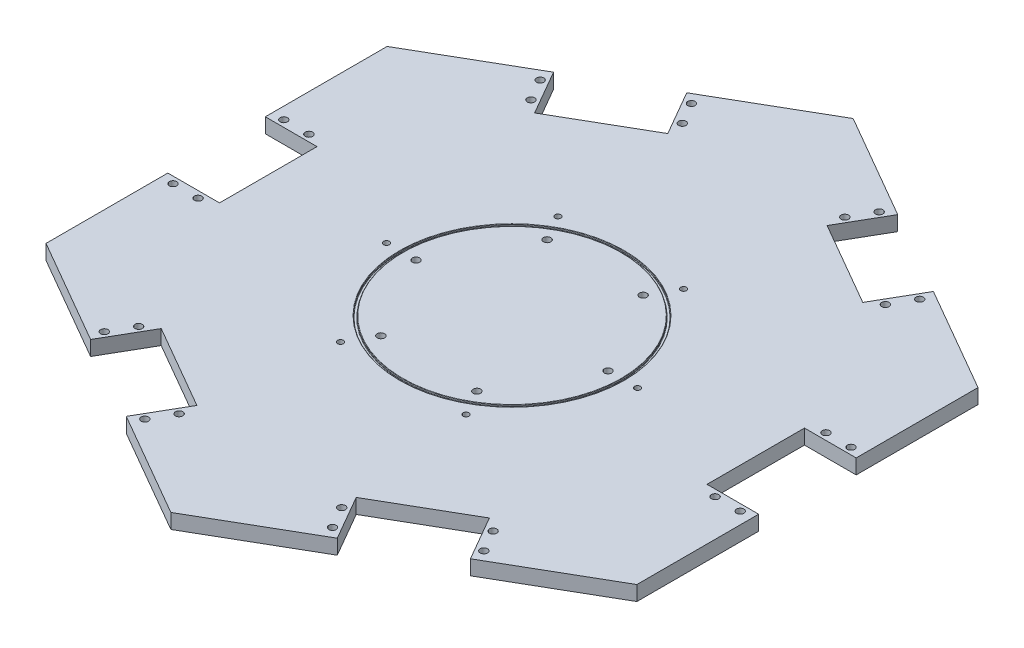
SolidWorks part; units mm, degrees
ref_plane "Front Plane" through (0, 0, 0) normal (0, 0, 1) x (1, 0, 0)
ref_plane "Top Plane" through (0, 0, 0) normal (0, 1, 0) x (1, 0, 0)
ref_plane "Right Plane" through (0, 0, 0) normal (1, 0, 0) x (0, 0, -1)
sketch "Sketch1" plane through (0, 0, 0) normal (0, 1, 0) x (1, 0, 0)
  line L0 (-200, 115.4701) -> (0, 230.9401)
  line L1 (-200, -115.4701) -> (200, -115.4701) construction
  line L2 (-200, -115.4701) -> (-200, 115.4701)
  line L3 (-200, 115.4701) -> (200, 115.4701) construction
  line L4 (200, -115.4701) -> (200, 115.4701)
  line L5 (-200, -115.4701) -> (200, 115.4701) construction
  line L6 (-200, 115.4701) -> (200, -115.4701) construction
  line L7 (0, 230.9401) -> (200, 115.4701)
  line L8 (200, -115.4701) -> (0, -230.9401)
  line L9 (0, -230.9401) -> (-200, -115.4701)
  point P0 (0, 0)
  point P8 (0, 245.7212)
  point P9 (0, 238.6781)
  dimension "D1" = 400
  dimension "D2" = 120
extrude "Boss-Extrude1" add sketch "Sketch1" along normal blind 10
sketch "Sketch2" plane through (0, 10, 0) normal (0, 1, 0) x (1, 0, 0)
  line L0 (175, -37.5) -> (175, 37.5) construction
  line L1 (200, 33) -> (165, 33)
  line L2 (200, 33) -> (200, -33)
  line L3 (200, -33) -> (165, -33)
  line L4 (165, 33) -> (165, -33)
  line L5 (128.5788, -156.7051) -> (111.0788, -126.3942)
  line L6 (200, 115.4701) -> (0, 230.9401)
  line L7 (0, 230.9401) -> (-200, 115.4701)
  line L8 (-200, 115.4701) -> (-200, -115.4701)
  line L9 (-200, -115.4701) -> (0, -230.9401)
  line L10 (0, -230.9401) -> (200, -115.4701)
  line L11 (200, -115.4701) -> (200, 115.4701)
  line L12 (200, 115.4701) -> (0, 230.9401)
  line L13 (0, 230.9401) -> (-200, 115.4701)
  line L14 (-200, 115.4701) -> (-200, -115.4701)
  line L15 (-200, -115.4701) -> (0, -230.9401)
  line L16 (0, -230.9401) -> (200, -115.4701)
  line L17 (200, -115.4701) -> (200, 115.4701)
  line L18 (111.0788, -126.3942) -> (53.9212, -159.3942)
  line L19 (71.4212, -189.7051) -> (53.9212, -159.3942)
  line L20 (-71.4212, -189.7051) -> (-53.9212, -159.3942)
  line L21 (-53.9212, -159.3942) -> (-111.0788, -126.3942)
  line L22 (-128.5788, -156.7051) -> (-111.0788, -126.3942)
  line L23 (-200, -33) -> (-165, -33)
  line L24 (-165, -33) -> (-165, 33)
  line L25 (-200, 33) -> (-165, 33)
  line L26 (-128.5788, 156.7051) -> (-111.0788, 126.3942)
  line L27 (-111.0788, 126.3942) -> (-53.9212, 159.3942)
  line L28 (-71.4212, 189.7051) -> (-53.9212, 159.3942)
  line L29 (71.4212, 189.7051) -> (53.9212, 159.3942)
  line L30 (53.9212, 159.3942) -> (111.0788, 126.3942)
  line L31 (128.5788, 156.7051) -> (111.0788, 126.3942)
  circle A0 centre (175, 37.5) radius 2.5
  circle A1 centre (192, 37.5) radius 2.5
  circle A2 centre (175, -37.5) radius 2.5
  circle A3 centre (192, -37.5) radius 2.5
  circle A4 centre (119.976, -132.8044) radius 2.5
  circle A5 centre (128.476, -147.5269) radius 2.5
  circle A6 centre (55.024, -170.3044) radius 2.5
  circle A7 centre (63.524, -185.0269) radius 2.5
  circle A8 centre (-55.024, -170.3044) radius 2.5
  circle A9 centre (-63.524, -185.0269) radius 2.5
  circle A10 centre (-119.976, -132.8044) radius 2.5
  circle A11 centre (-128.476, -147.5269) radius 2.5
  circle A12 centre (-175, -37.5) radius 2.5
  circle A13 centre (-192, -37.5) radius 2.5
  circle A14 centre (-175, 37.5) radius 2.5
  circle A15 centre (-192, 37.5) radius 2.5
  circle A16 centre (-119.976, 132.8044) radius 2.5
  circle A17 centre (-128.476, 147.5269) radius 2.5
  circle A18 centre (-55.024, 170.3044) radius 2.5
  circle A19 centre (-63.524, 185.0269) radius 2.5
  circle A20 centre (55.024, 170.3044) radius 2.5
  circle A21 centre (63.524, 185.0269) radius 2.5
  circle A22 centre (119.976, 132.8044) radius 2.5
  circle A23 centre (128.476, 147.5269) radius 2.5
  point P10 (165, 0)
  point P20 (175, 0)
  point P83 (0, 0)
  dimension "D6" = 5
  dimension "D2" = 66
  dimension "D3" = 35
  dimension "D4" = 75
  dimension "D5" = 17
  dimension "D7" = 10
  dimension "D1" = 0
  dimension "D8" = 6
extrude "Cut-Extrude1" cut sketch "Sketch2" against normal through all both and the other way through all
sketch "Sketch3" plane through (0, 0, 0) normal (0, 0, 1) x (1, 0, 0)
  line L0 (74.11, 10) -> (74.11, 8.984)
  line L1 (0, 10) -> (71.4212, 10) construction
  line L2 (74.364, 8.73) -> (75.636, 8.73)
  line L3 (75.89, 8.984) -> (75.89, 10)
  line L4 (75.89, 10) -> (74.11, 10)
  line L5 (0, 10) -> (0, 0) construction
  arc A0 (75.636, 8.73) -> (75.89, 8.984) centre (75.636, 8.984) ccw
  arc A1 (74.11, 8.984) -> (74.364, 8.73) centre (74.364, 8.984) ccw
  point P8 (75, 8.73)
  dimension "D4" = 0.254
  dimension "D1" = 75
  dimension "D2" = 1.78
  dimension "D3" = 1.27
sketch "Sketch4" plane through (0, 10, 0) normal (0, 1, 0) x (1, 0, 0)
  circle A0 centre (0, 0) radius 75
  dimension "D1" = 150
sweep "Cut-Sweep1" cut profiles "Sketch3" path "Sketch4"
fillet "Fillet1" radius 0.254 2 edges at (74.11, 10, 0) (75.89, 10, 0)
sketch "Sketch5" plane through (0, 10, 0) normal (0, 1, 0) x (1, 0, 0)
  line L0 (0, 0) -> (85, 0) construction
  circle A0 centre (85, 0) radius 2
  circle A1 centre (42.5, -73.6122) radius 2
  circle A2 centre (-42.5, -73.6122) radius 2
  circle A3 centre (-85, 0) radius 2
  circle A4 centre (-42.5, 73.6122) radius 2
  circle A5 centre (42.5, 73.6122) radius 2
  circle A6 centre (65, 0) radius 2.5
  circle A7 centre (32.5, -56.2917) radius 2.5
  circle A8 centre (-32.5, -56.2917) radius 2.5
  circle A9 centre (-65, 0) radius 2.5
  circle A10 centre (-32.5, 56.2917) radius 2.5
  circle A11 centre (32.5, 56.2917) radius 2.5
  point P16 (0, 0)
  point P29 (0, 0)
  dimension "D2" = 4
  dimension "D5" = 5
  dimension "D1" = 85
  dimension "D4" = 65
  dimension "D3" = 6
  dimension "D6" = 6
extrude "Cut-Extrude2" cut sketch "Sketch5" against normal through all both and the other way through all
